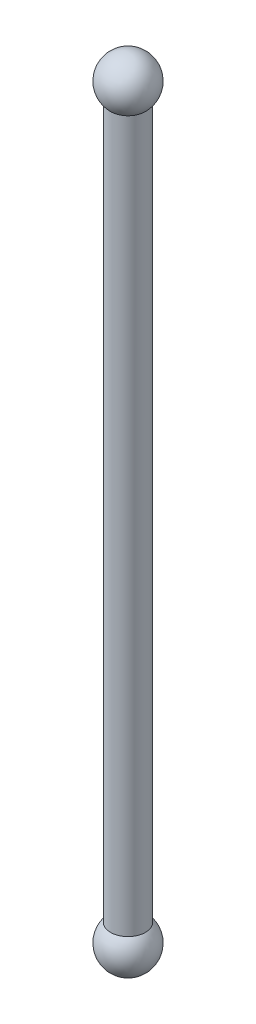
SolidWorks part; units mm, degrees
ref_plane "Front Plane" through (0, 0, 0) normal (0, 0, 1) x (1, 0, 0)
ref_plane "Top Plane" through (0, 0, 0) normal (0, 1, 0) x (1, 0, 0)
ref_plane "Right Plane" through (0, 0, 0) normal (1, 0, 0) x (0, 0, -1)
sketch "Sketch1" plane through (0, 0, 0) normal (0, 0, 1) x (1, 0, 0)
  line L0 (0, 300) -> (0, 310)
  line L1 (0, 0) -> (7, 0)
  line L2 (0, 0) -> (0, 300)
  line L3 (0, 300) -> (7, 300)
  line L4 (7, 0) -> (7, 300)
  line L5 (0, 0) -> (0, -10)
  arc A0 (0, -10) -> (0, 10) centre (0, 0) ccw
  arc A1 (0, 290) -> (0, 310) centre (0, 300) ccw
  dimension "D1" = 20
  dimension "D2" = 300
  dimension "D3" = 7
revolve "Revolve1" add sketch "Sketch1" angle 360 about L2
